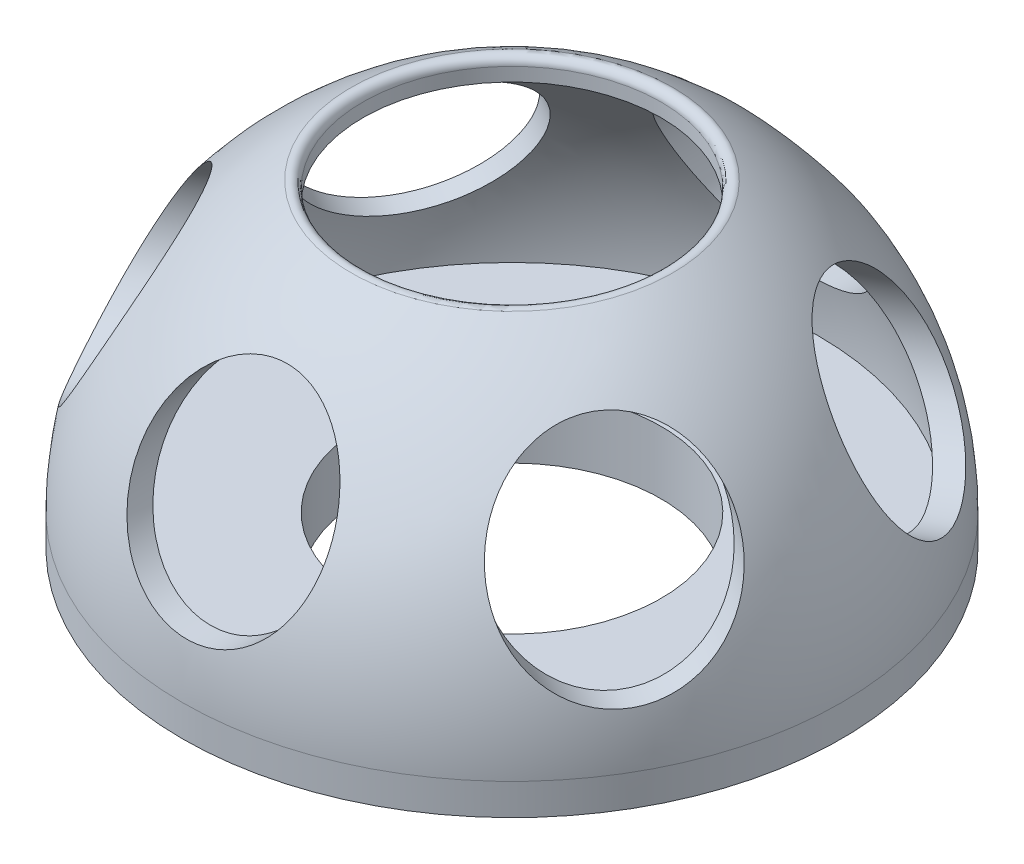
SolidWorks part; units mm, degrees
ref_plane "Front Plane" through (0, 0, 0) normal (0, 0, 1) x (1, 0, 0)
ref_plane "Top Plane" through (0, 0, 0) normal (0, 1, 0) x (1, 0, 0)
ref_plane "Right Plane" through (0, 0, 0) normal (1, 0, 0) x (0, 0, -1)
sketch "Sketch1" plane through (0, 2, 0) normal (0, 1, 0) x (1, 0, 0)
  circle A0 centre (0, 0) radius 11
  arc A1 (11.4991, 0.1463) -> (11.0418, 3.2139) centre (0, 0) ccw construction
  circle A2 centre (0, 0) radius 9.5
  dimension "D1" = 0.5
  dimension "D2" = 1.5
extrude "Boss-Extrude1" add sketch "Sketch1" against normal blind 2
sketch "Sketch2" plane through (0, 2, 0) normal (0, 1, 0) x (1, 0, 0)
  circle A0 centre (0, 0) radius 21
  circle A1 centre (0, 0) radius 13 construction
  circle A2 centre (0, 0) radius 9.5
  circle A3 centre (0, 0) radius 9.5 construction
  dimension "D1" = 8
extrude "Boss-Extrude2" add sketch "Sketch2" along normal blind 2
sketch "Sketch3" plane through (0, 4, 0) normal (0, 1, 0) x (1, 0, 0)
  line L0 (-19.5, 0) -> (-21, 0)
  line L1 (19.5, 0) -> (21, 0)
  arc A0 (-21, 0) -> (21, 0) centre (0, 0) cw
  circle A1 centre (0, 0) radius 21 construction
  arc A2 (-19.5, 0) -> (19.5, 0) centre (0, 0) cw
  dimension "D1" = 1.5
revolve "Revolve1" add sketch "Sketch3" angle 180 about L0
sketch "Sketch4" plane through (0, 0, 0) normal (0, -1, 0) x (1, 0, 0)
  circle A0 centre (0, 0) radius 9.5
  circle A1 centre (0, 0) radius 9.5 construction
extrude "Cut-Extrude1" cut sketch "Sketch4" against normal through all
sketch "Sketch5" plane through (0, 0, 0) normal (0, 0, 1) x (1, 0, 0)
  line L0 (0, 22.7283) -> (0, 4) construction
  line L1 (21, 4) -> (-21, 4) construction
  line L2 (9.5, 22.7283) -> (-9.5, 22.7283) construction
  circle A0 centre (0, 13.3642) radius 6
  dimension "D1" = 12
extrude "Cut-Extrude2" cut sketch "Sketch5" against normal through all both and the other way through all
pattern_circular "CirPattern1" count 3 over 360 about axis through (0, 22.7283, 0) along (0, -1, 0) of "Cut-Extrude2"
fillet "Fillet1" radius 0.5 1 edges at (0, 22.7283, -9.5)
